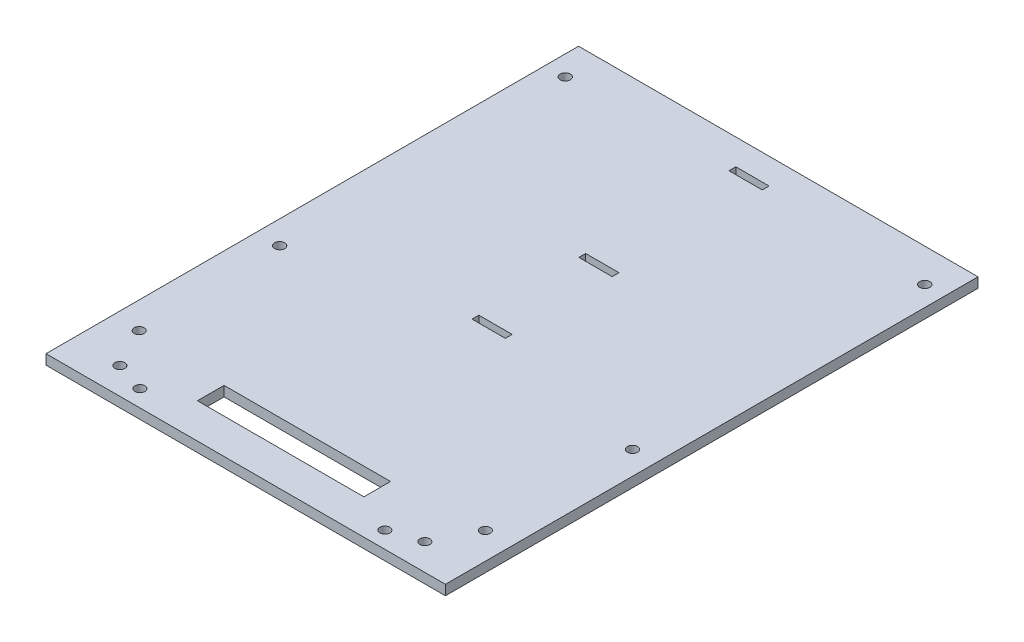
SolidWorks part; units mm, degrees
ref_plane "Front Plane" through (0, 0, 0) normal (0, 0, 1) x (1, 0, 0)
ref_plane "Top Plane" through (0, 0, 0) normal (0, 1, 0) x (1, 0, 0)
ref_plane "Right Plane" through (0, 0, 0) normal (1, 0, 0) x (0, 0, -1)
sketch "Sketch1" plane through (0, 0, 0) normal (0, 1, 0) x (1, 0, 0)
  line L1 (60, -80) -> (-60, -80)
  line L2 (60, -80) -> (60, 80)
  line L3 (60, 80) -> (-60, 80)
  line L4 (-60, -80) -> (-60, 80)
  line L5 (60, -80) -> (-60, 80) construction
  line L6 (60, 80) -> (-60, -80) construction
  point P0 (0, 0)
  dimension "D1" = 160
  dimension "D2" = 120
extrude "Boss-Extrude1" add sketch "Sketch1" along normal blind 3
sketch "Sketch2" plane through (0, 3, 0) normal (0, 1, 0) x (1, 0, 0)
  line L0 (0, 0) -> (0, 80) construction
  line L1 (60, 80) -> (-60, 80) construction
  line L2 (-60, 80) -> (-60, -80) construction
  circle A0 centre (-53, -16.81) radius 1.525
  circle A1 centre (-54, 70) radius 1.525
  circle A2 centre (53, -16.81) radius 1.525
  circle A3 centre (54, 70) radius 1.525
  dimension "D1" = 10
  dimension "D2" = 3.05
  dimension "D3" = 6
  dimension "D4" = 3.05
  dimension "D5" = 7
  dimension "D6" = 86.81
extrude "Cut-Extrude1" cut sketch "Sketch2" against normal through all
sketch "Sketch3" plane through (0, 3, 0) normal (0, 1, 0) x (1, 0, 0)
  line L0 (-5, 27.14) -> (5, 27.14)
  line L1 (-5, -4.96) -> (5, -4.96)
  line L2 (-5, -4.96) -> (-5, -7.01)
  line L3 (-5, -7.01) -> (5, -7.01)
  line L4 (5, -4.96) -> (5, -7.01)
  line L5 (-5, -4.96) -> (5, -7.01) construction
  line L6 (-5, -7.01) -> (5, -4.96) construction
  line L7 (-5, 27.14) -> (-5, 25.09)
  line L8 (-5, 25.09) -> (5, 25.09)
  line L9 (5, 27.14) -> (5, 25.09)
  line L11 (-5, 72.24) -> (5, 72.24)
  line L12 (-5, 72.24) -> (-5, 70.19)
  line L13 (-5, 70.19) -> (5, 70.19)
  line L14 (-5, 59.24) -> (5, 59.24) [skipped]
  line L15 (-5, 59.24) -> (-5, 57.19) [skipped]
  line L16 (-5, 57.19) -> (5, 57.19) [skipped]
  line L17 (5, 59.24) -> (5, 57.19) [skipped]
  line L18 (5, 72.24) -> (5, 70.19)
  line L19 (-5, 72.24) -> (5, 70.19) construction
  line L20 (-5, 70.19) -> (5, 72.24) construction
  circle A0 centre (-53, -16.81) radius 1.525 construction
  point P0 (0, -5.985)
  point P8 (0, 71.215)
  dimension "D2" = 9.8
  dimension "D1" = 2.05
  dimension "D3" = 10
  dimension "D4" = 0
  dimension "D6" = 2.05
  dimension "D7" = 10
  dimension "D8" = 0
  dimension "D9" = 43.05
  dimension "D10" = 30.05
  dimension "D5" = 3
extrude "Cut-Extrude2" cut sketch "Sketch3" against normal through all
sketch "Sketch4" plane through (0, 3, 0) normal (0, 1, 0) x (1, 0, 0)
  line L0 (-60, -80) -> (60, -80) construction
  line L1 (-60, 80) -> (-60, -80) construction
  line L2 (0, 0) -> (0, -80) construction
  circle A1 centre (-52, -60) radius 1.5
  circle A2 centre (-45.8153, -72) radius 1.5
  circle A3 centre (45.8153, -72) radius 1.5
  circle A4 centre (52, -60) radius 1.5
  dimension "D1" = 3
  dimension "D2" = 3
  dimension "D4" = 8
  dimension "D5" = 13.5
  dimension "D6" = 8
  dimension "D3" = 20
extrude "Cut-Extrude3" cut sketch "Sketch4" against normal blind 3
sketch "Sketch5" plane through (0, 3, 0) normal (0, 1, 0) x (1, 0, 0)
  line L0 (0, 0) -> (0, -80) construction
  line L2 (25, -69.5) -> (-25, -69.5)
  line L3 (25, -69.5) -> (25, -61.5)
  line L4 (25, -61.5) -> (-25, -61.5)
  line L5 (-25, -69.5) -> (-25, -61.5)
  line L6 (25, -69.5) -> (-25, -61.5) construction
  line L7 (-60, -80) -> (60, -80) construction
  line L8 (25, -61.5) -> (-25, -69.5) construction
  circle A0 centre (-36.8, -75) radius 1.5
  circle A1 centre (36.8, -75) radius 1.5
  point P0 (0, -65.5)
  dimension "D3" = 3
  dimension "D4" = 5.5
  dimension "D5" = 5
  dimension "D1" = 8
  dimension "D2" = 50
  dimension "D6" = 36.8
extrude "Cut-Extrude4" cut sketch "Sketch5" against normal blind 3
